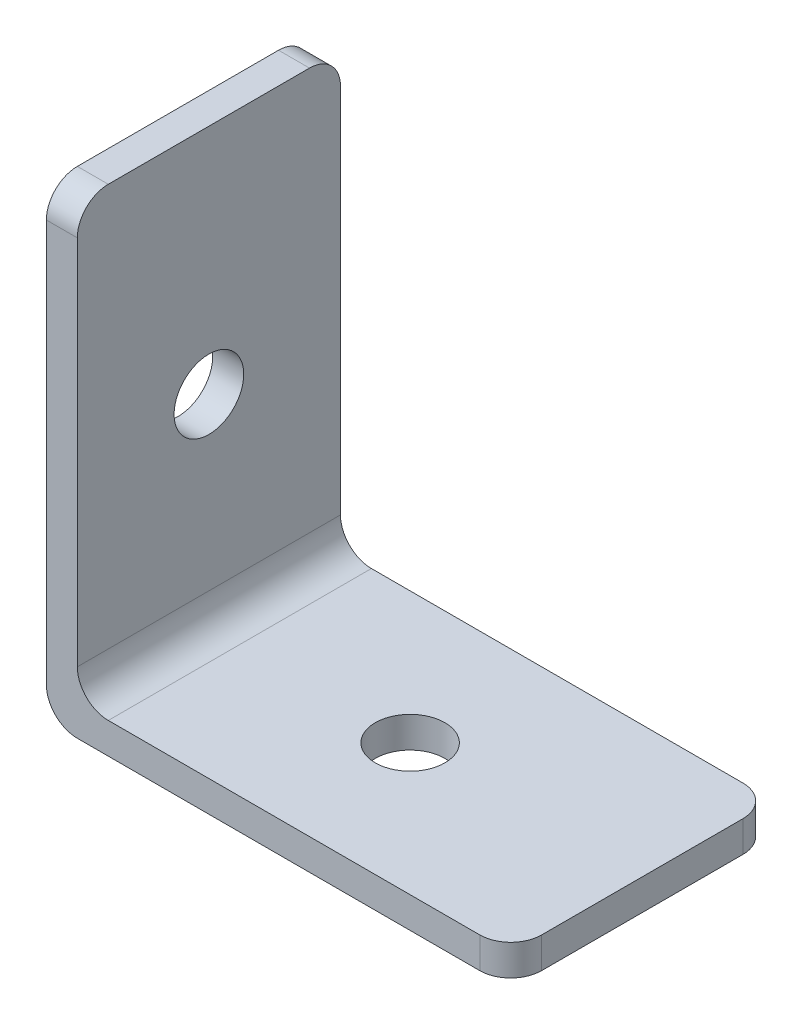
SolidWorks part; units mm, degrees
ref_plane "Front Plane" through (0, 0, 0) normal (0, 0, 1) x (1, 0, 0)
ref_plane "Top Plane" through (0, 0, 0) normal (0, 1, 0) x (1, 0, 0)
ref_plane "Right Plane" through (0, 0, 0) normal (1, 0, 0) x (0, 0, -1)
sketch "Sketch1" plane through (0, 0, 0) normal (0, 0, 1) x (1, 0, 0)
  line L0 (0, 30) -> (0, 0)
  line L1 (0, 0) -> (30, 0)
  dimension "D1" = 30
  dimension "D2" = 30
extrude "Extrude-Thin1" add sketch "Sketch1" along normal blind 17 thin thin type one direction reverse wall 2
fillet "Fillet1" radius 2 4 edges at (30, 1, 17) (30, 1, 0) (1, 30, 17) (1, 30, 0)
fillet "Fillet2" radius 2 2 edges at (0, 0, 8.5) (2, 2, 8.5)
sketch "Sketch2" plane through (0, 0, 0) normal (-1, 0, 0) x (0, 0, 1)
  line L1 (15, 30) -> (2, 30) construction
  line L2 (17, 28) -> (17, 2) construction
  circle A0 centre (8.5, 15) radius 2.25
  dimension "D1" = 15
  dimension "D2" = 8.5
  dimension "D3" = 4.5
extrude "Cut-Extrude1" cut sketch "Sketch2" against normal blind 10
sketch "Sketch4" plane through (0, 0, 0) normal (0, -1, 0) x (1, 0, 0)
  line L0 (2, 17) -> (28, 17) construction
  line L1 (30, 15) -> (30, 2) construction
  circle A0 centre (15, 8.5) radius 2.25
  dimension "D1" = 4.5
  dimension "D2" = 8.5
  dimension "D3" = 15
extrude "Cut-Extrude2" cut sketch "Sketch4" against normal blind 10
